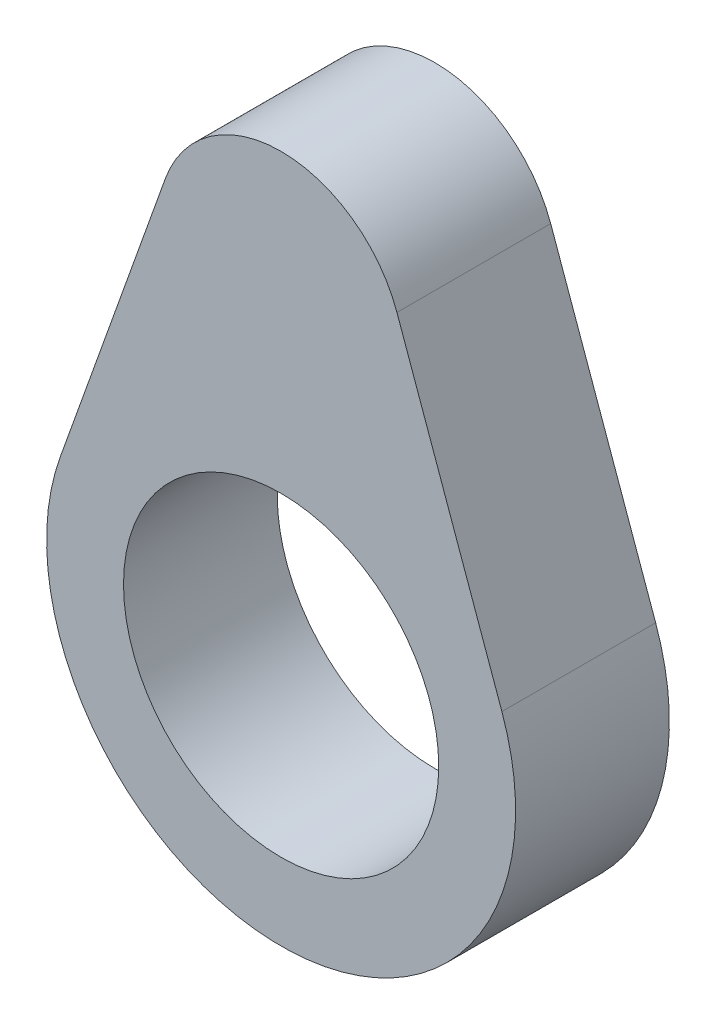
SolidWorks part; units mm, degrees
ref_plane "Front Plane" through (0, 0, 0) normal (0, 0, 1) x (1, 0, 0)
ref_plane "Top Plane" through (0, 0, 0) normal (0, 1, 0) x (1, 0, 0)
ref_plane "Right Plane" through (0, 0, 0) normal (1, 0, 0) x (0, 0, -1)
sketch "Sketch1" plane through (0, 0, 0) normal (0, 0, 1) x (1, 0, 0)
  line L0 (0, 7.625) -> (0, 22.625)
  line L1 (0, 22.625) -> (-7.1789, 2.5698)
  line L2 (0, 22.625) -> (7.1789, 2.5698)
  circle A0 centre (0, 0) radius 5.125
  circle A1 centre (0, 0) radius 7.625
extrude "Boss-Extrude1" add sketch "Sketch1" along normal blind 5 contours A1 A0 | A1 L0 L1 | A1 L2 L0
fillet "Fillet1" radius 4 1 edges at (0, 22.625, 2.5)
